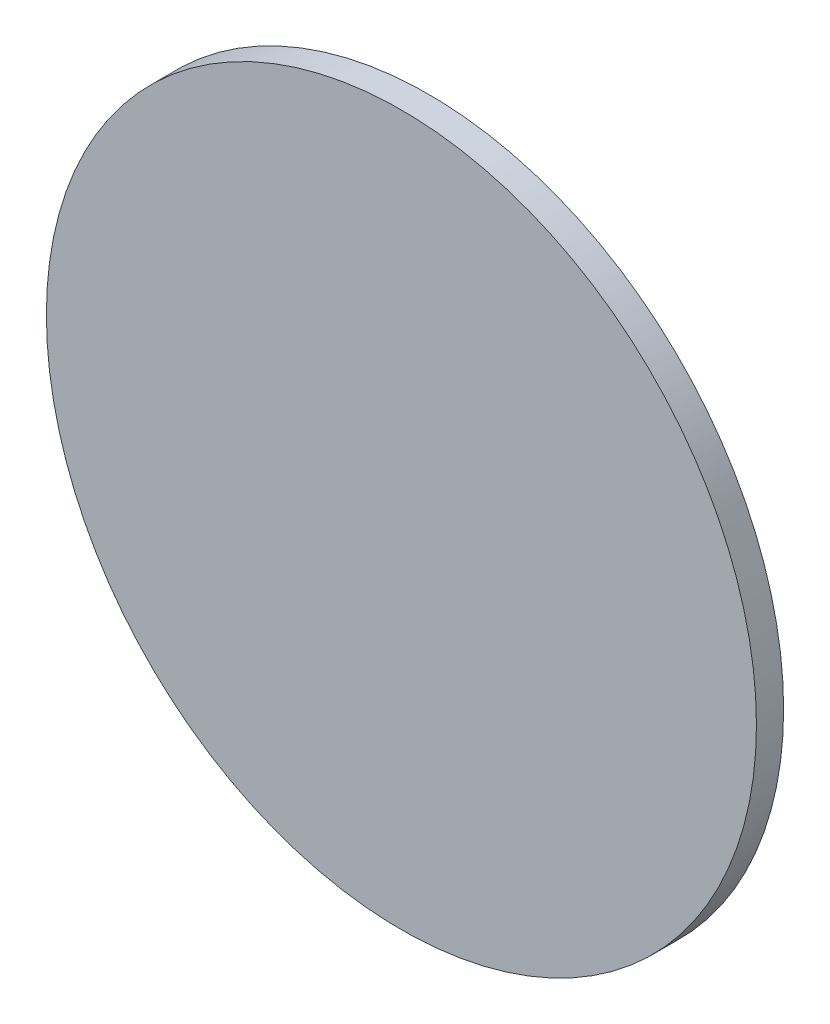
SolidWorks part; units mm, degrees
ref_plane "Спереди" through (0, 0, 0) normal (0, 0, 1) x (1, 0, 0)
ref_plane "Сверху" through (0, 0, 0) normal (0, 1, 0) x (1, 0, 0)
ref_plane "Справа" through (0, 0, 0) normal (1, 0, 0) x (0, 0, -1)
sketch "Эскиз1" plane through (0, 0, 0) normal (0, 0, 1) x (1, 0, 0)
  circle A0 centre (0, 0) radius 20.9
  dimension "D1" = 41.8
extrude "Бобышка-Вытянуть1" add sketch "Эскиз1" along normal blind 1.6
